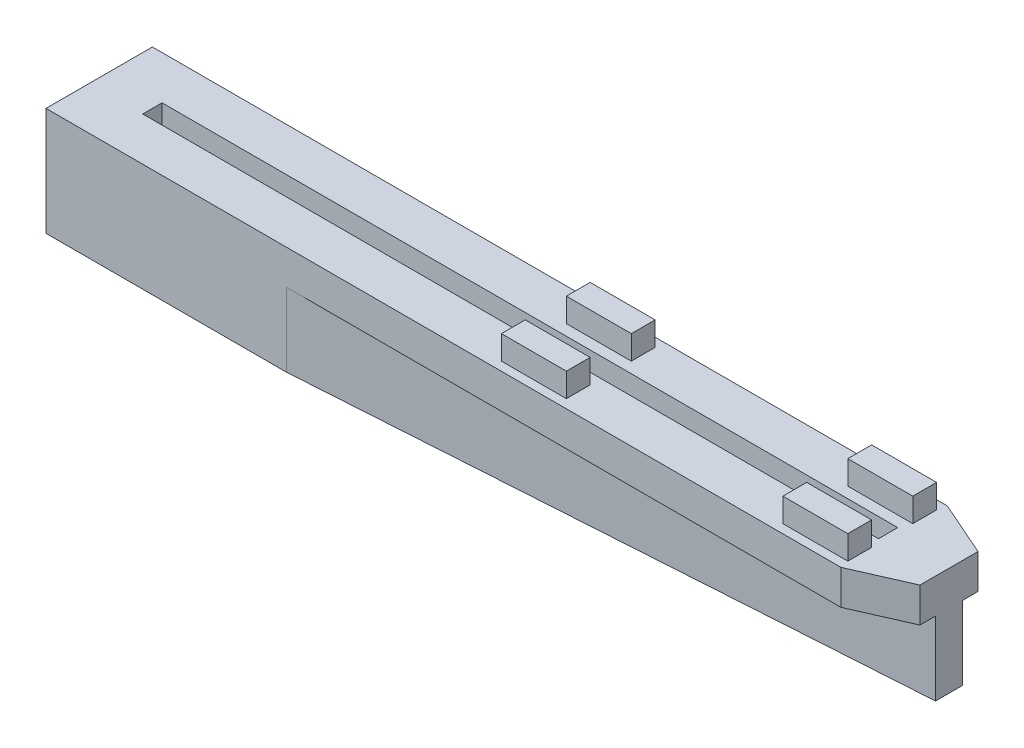
SolidWorks part; units mm, degrees
ref_plane "Front Plane" through (0, 0, 0) normal (0, 0, 1) x (1, 0, 0)
ref_plane "Top Plane" through (0, 0, 0) normal (0, 1, 0) x (1, 0, 0)
ref_plane "Right Plane" through (0, 0, 0) normal (1, 0, 0) x (0, 0, -1)
sketch "Sketch1" plane through (0, 0, 0) normal (0, 1, 0) x (1, 0, 0)
  line L0 (67.4834, 1.0876) -> (67.4834, 10.5876) construction
  line L1 (-43.1536, 18.12) -> (140.4332, 18.12)
  line L2 (-43.1536, 18.12) -> (-43.1536, -6.4447)
  line L3 (-43.1536, -6.4447) -> (140.4332, -6.4447)
  line L4 (153.0942, 12.5424) -> (153.0942, -0.8672)
  line L5 (59.9834, 1.0876) -> (74.9834, 1.0876) construction
  line L6 (59.9834, 10.5876) -> (74.9834, 10.5876) construction
  line L7 (67.4834, 5.8376) -> (13.5512, 5.8376) construction
  line L8 (153.0942, 5.8376) -> (23.5539, 5.8376) construction
  line L9 (-43.1536, 98.3376) -> (-43.1536, -86.6624) construction
  line L11 (140.4332, 18.12) -> (153.0942, 12.5424)
  line L12 (140.4332, -6.4447) -> (153.0942, -0.8672)
extrude "Boss-Extrude1" add sketch "Sketch1" along normal blind 5
sketch "Sketch2" plane through (0, 0, 0) normal (0, -1, 0) x (1, 0, 0)
  line L0 (153.0942, -5.8376) -> (143.3615, -5.8376) construction
  line L1 (139.0418, -8.0666) -> (-30.8596, -8.0666)
  line L2 (139.0418, -8.0666) -> (139.0418, -3.6087)
  line L3 (139.0418, -3.6087) -> (-30.8596, -3.6087)
  line L4 (-30.8596, -8.0666) -> (-30.8596, -3.6087)
  line L5 (153.0942, 0.8672) -> (153.0942, -12.5424) construction
  line L6 (139.0418, -5.8376) -> (124.9281, -5.8376) construction
extrude "Cut-Extrude1" cut sketch "Sketch2" against normal blind 26
sketch "Sketch3" plane through (0, 5, 0) normal (0, 1, 0) x (1, 0, 0)
  line L0 (124.9834, 10.5876) -> (139.9834, 10.5876) construction
  line L1 (124.9834, 16.0876) -> (124.9834, 10.5876) construction
  line L2 (139.9834, 16.0876) -> (139.9834, 10.5876) construction
  line L3 (124.9834, 16.0876) -> (139.9834, 16.0876) construction
  line L4 (124.9834, 10.5876) -> (139.9834, 10.5876)
  line L5 (124.9834, 16.0876) -> (124.9834, 10.5876)
  line L6 (139.9834, 16.0876) -> (139.9834, 10.5876)
  line L7 (124.9834, 16.0876) -> (139.9834, 16.0876)
  line L8 (139.9834, -4.4124) -> (139.9834, 1.0876) construction
  line L9 (124.9834, -4.4124) -> (139.9834, -4.4124) construction
  line L10 (124.9834, -4.4124) -> (124.9834, 1.0876) construction
  line L11 (124.9834, 1.0876) -> (139.9834, 1.0876) construction
  line L12 (139.9834, -4.4124) -> (139.9834, 1.0876)
  line L13 (124.9834, -4.4124) -> (139.9834, -4.4124)
  line L14 (124.9834, -4.4124) -> (124.9834, 1.0876)
  line L15 (124.9834, 1.0876) -> (139.9834, 1.0876)
  line L16 (59.9834, -4.4124) -> (59.9834, 1.0876) construction
  line L17 (59.9834, -4.4124) -> (74.9834, -4.4124) construction
  line L18 (74.9834, -4.4124) -> (74.9834, 1.0876) construction
  line L19 (59.9834, 1.0876) -> (74.9834, 1.0876) construction
  line L20 (59.9834, -4.4124) -> (59.9834, 1.0876)
  line L21 (59.9834, -4.4124) -> (74.9834, -4.4124)
  line L22 (74.9834, -4.4124) -> (74.9834, 1.0876)
  line L23 (59.9834, 1.0876) -> (74.9834, 1.0876)
  line L24 (59.9834, 16.0876) -> (59.9834, 10.5876) construction
  line L25 (74.9834, 16.0876) -> (74.9834, 10.5876) construction
  line L26 (59.9834, 16.0876) -> (74.9834, 16.0876) construction
  line L27 (59.9834, 10.5876) -> (74.9834, 10.5876) construction
  line L28 (59.9834, 16.0876) -> (59.9834, 10.5876)
  line L29 (74.9834, 16.0876) -> (74.9834, 10.5876)
  line L30 (59.9834, 16.0876) -> (74.9834, 16.0876)
  line L31 (59.9834, 10.5876) -> (74.9834, 10.5876)
extrude "Boss-Extrude2" add sketch "Sketch3" along normal up to surface (5.5 mm away)
sketch "Sketch4" plane through (0, 0, 0) normal (0, -1, 0) x (1, 0, 0)
  line L0 (140.4332, -18.12) -> (-43.1536, -18.12) construction
  line L1 (-43.1536, -18.12) -> (140.4332, -18.12)
  line L2 (-43.1536, -18.12) -> (-43.1536, 6.4447)
  line L3 (-43.1536, 6.4447) -> (140.4332, 6.4447)
  line L5 (-43.1536, -18.12) -> (-43.1536, 6.4447) construction
  line L7 (-30.8596, -8.0666) -> (-30.8596, -3.6087)
  line L8 (-30.8596, -3.6087) -> (139.0418, -3.6087)
  line L10 (-30.8596, -8.0666) -> (139.0418, -8.0666)
  line L25 (153.0942, -12.5424) -> (140.4332, -18.12) construction
  line L26 (153.0942, 0.8672) -> (153.0942, -12.5424) construction
  line L27 (140.4332, 6.4447) -> (153.0942, 0.8672) construction
  line L28 (153.0942, -12.5424) -> (140.4332, -18.12)
  line L29 (153.0942, 0.8672) -> (153.0942, -12.5424)
  line L30 (140.4332, 6.4447) -> (153.0942, 0.8672)
extrude "Boss-Extrude3" add sketch "Sketch4" along normal blind 20
sketch "Sketch7" plane through (0, -20, 0) normal (0, -1, 0) x (1, 0, 0)
  line L0 (153.0942, -5.8376) -> (159.943, -5.8376) construction
  line L1 (153.0942, -12.5424) -> (153.0942, 0.8672) construction
  line L5 (-43.1536, -18.12) -> (140.4332, -18.12) construction
  line L10 (140.4332, 6.4447) -> (-43.1536, 6.4447) construction
  line L12 (12.3871, -18.12) -> (140.4332, -18.12)
  line L13 (140.4332, -18.12) -> (153.0942, -12.5424)
  line L14 (153.0942, -12.5424) -> (153.0942, -8.9376)
  line L15 (153.0942, -2.7376) -> (153.0942, 0.8672)
  line L16 (153.0942, 0.8672) -> (140.4332, 6.4447)
  line L17 (140.4332, 6.4447) -> (12.3871, 6.4447)
  line L21 (153.0942, -8.9376) -> (12.3871, -18.12)
  line L22 (153.0942, -2.7376) -> (12.3871, 6.4447)
  dimension "D1" = 3.1
  dimension "D2" = 3.1
extrude "Cut-Extrude5" cut sketch "Sketch7" against normal blind 17
